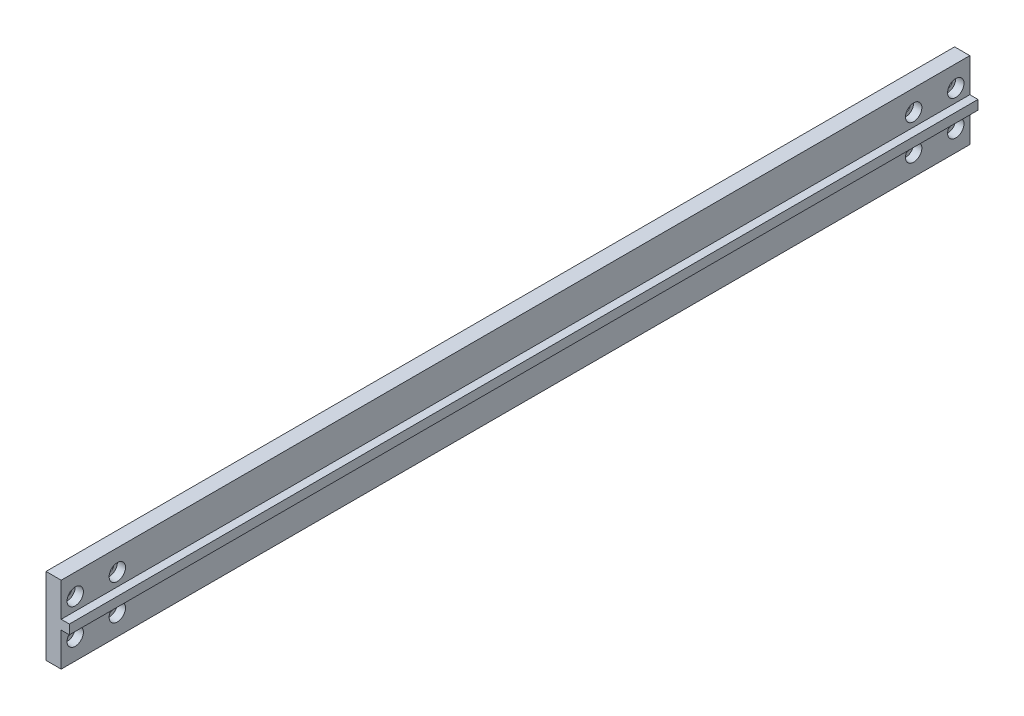
SolidWorks part; units mm, degrees
material "1.4000 (X6Cr13)"
ref_plane "前视基准面" through (0, 0, 0) normal (0, 0, 1) x (1, 0, 0)
ref_plane "上视基准面" through (0, 0, 0) normal (0, 1, 0) x (1, 0, 0)
ref_plane "右视基准面" through (0, 0, 0) normal (1, 0, 0) x (0, 0, -1)
sketch "草图1" plane through (0, 0, 0) normal (0, 0, 1) x (1, 0, 0)
  line L0 (0, 16.475) -> (0, -16.475)
  line L1 (0, -16.475) -> (6.5, -16.475)
  line L2 (0, 16.475) -> (6.5, 16.475)
  line L3 (6.5, 16.475) -> (6.5, 2)
  line L5 (6.5, 2) -> (10, 2)
  line L6 (10, 2) -> (10, -2)
  line L7 (10, -2) -> (6.5, -2)
  line L9 (6.5, -2) -> (6.5, -16.475)
  point P4 (0, 0)
  dimension "D1" = 6.5
  dimension "D2" = 32.95
  dimension "D3" = 4
  dimension "D4" = 3.5
  dimension "D5" = 14.475
extrude "凸台-拉伸1" add sketch "草图1" along normal blind 388.6
sketch "草图2" plane through (0, 0, 0) normal (-1, 0, 0) x (0, 0, 1)
  line L5 (6, 7.5) -> (382.6, 7.5) construction
  line L6 (6, 7.5) -> (6, -7.5) construction
  line L7 (6, -7.5) -> (382.6, -7.5) construction
  line L8 (382.6, 7.5) -> (382.6, -7.5) construction
  line L9 (6, 7.5) -> (382.6, -7.5) construction
  line L10 (6, -7.5) -> (382.6, 7.5) construction
  line L11 (24, 7.5) -> (364.6, 7.5) construction
  line L12 (24, 7.5) -> (24, -7.5) construction
  line L13 (24, -7.5) -> (364.6, -7.5) construction
  line L14 (364.6, 7.5) -> (364.6, -7.5) construction
  line L15 (24, 7.5) -> (364.6, -7.5) construction
  line L16 (24, -7.5) -> (364.6, 7.5) construction
  point P0 (194.3, 0)
  point P5 (194.3, 0)
  point P7 (194.3, 0)
  dimension "D1" = 376.6
  dimension "D2" = 15
  dimension "D3" = 194.3
  dimension "D4" = 15
  dimension "D5" = 340.6
hole_wizard "打孔尺寸(%根据)内六角圆柱头螺钉的类型1" positions "草图6" profile "草图7" counterbore size "M4" standard "GB" end condition through all
sketch "草图6" plane through (6.5, 0, 0) normal (1, 0, 0) x (0, 0, -1)
  point P0 (-382.6, -7.5)
  point P3 (-364.6, -7.5)
  point P6 (-364.6, 7.5)
  point P9 (-382.6, 7.5)
  point P12 (-24, 7.5)
  point P15 (-24, -7.5)
  point P18 (-6, -7.5)
  point P21 (-6, 7.5)
sketch "草图7" plane through (6.5, -7.5, 382.6) normal (0, 1, 0) x (0, 0, -1)
  line L0 (0, 0) -> (0, 6.5)
  line L1 (0, 6.5) -> (2, 6.5)
  line L3 (2, 6.5) -> (2, 3.5)
  line L4 (2, 3.5) -> (3.5, 3.5)
  line L5 (3.5, 3.5) -> (3.5, 0)
  line L7 (3.5, 0) -> (0, 0)
  line L11 (0, -6.35) -> (0, 107.95) construction
  dimension "通孔孔直径" = 4
  dimension "通孔孔深度" = 6.5
  dimension "柱形沉头孔直径" = 7
  dimension "柱形沉头孔深度" = 3.5
